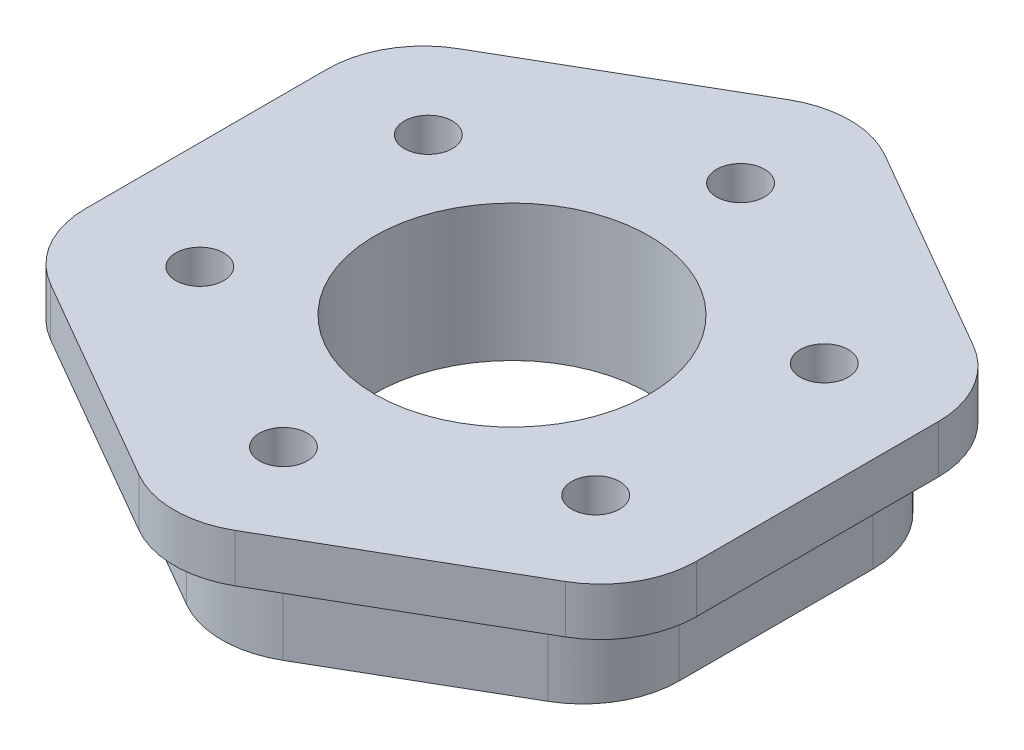
SolidWorks part; units mm, degrees
ref_plane "Front" through (0, 0, 0) normal (0, 0, 1) x (1, 0, 0)
ref_plane "Top" through (0, 0, 0) normal (0, 1, 0) x (1, 0, 0)
ref_plane "Right" through (0, 0, 0) normal (1, 0, 0) x (0, 0, -1)
sketch "Sketch1" plane through (0, 0, 0) normal (0, 1, 0) x (1, 0, 0)
  line L0 (0, 0) -> (0, -36.7195) construction
  line L1 (31.8, 18.3597) -> (0, 36.7195)
  line L2 (0, 36.7195) -> (-31.8, 18.3597)
  line L3 (-31.8, 18.3597) -> (-31.8, -18.3597)
  line L4 (-31.8, -18.3597) -> (0, -36.7195)
  line L5 (0, -36.7195) -> (31.8, -18.3597)
  line L6 (31.8, -18.3597) -> (31.8, 18.3597)
  circle A0 centre (0, 0) radius 31.8 construction
  dimension "D1" = 63.6
extrude "Boss-Extrude1" add sketch "Sketch1" along normal blind 5
fillet "Fillet1" radius 10 6 edges at (31.8, 2.5, -18.3597) (0, 2.5, -36.7195) (-31.8, 2.5, -18.3597) (-31.8, 2.5, 18.3597) (0, 2.5, 36.7195) (31.8, 2.5, 18.3597)
sketch "Sketch2" plane through (0, 5, 0) normal (0, 1, 0) x (1, 0, 0)
  line L0 (0, 23.8) -> (0, -23.8) construction
  line L1 (-20.6114, 11.9) -> (-20.6114, -11.9) construction
  line L2 (20.6114, 11.9) -> (20.6114, -11.9) construction
  line L3 (-20.6114, -11.9) -> (20.6114, -11.9) construction
  line L4 (-20.6114, -11.9) -> (20.6114, 11.9) construction
  line L5 (-20.6114, 11.9) -> (20.6114, 11.9) construction
  line L7 (20.6114, -11.9) -> (-20.6114, 11.9) construction
  circle A0 centre (0, 23.8) radius 2.5
  circle A2 centre (20.6114, 11.9) radius 2.5
  circle A3 centre (20.6114, -11.9) radius 2.5
  circle A4 centre (0, -23.8) radius 2.5
  circle A5 centre (-20.6114, -11.9) radius 2.5
  circle A6 centre (-20.6114, 11.9) radius 2.5
  circle A7 centre (0, 0) radius 14.2875
  point P21 (0, 0)
  dimension "D2" = 5
  dimension "D4" = 28.575
  dimension "D1" = 23.8
  dimension "D3" = 6
sketch "Sketch3" plane through (0, 0, 0) normal (0, -1, 0) x (1, 0, 0)
  line L0 (-20.6114, 11.9) -> (20.6114, -11.9) construction
  line L1 (27.5, 15.8771) -> (0, 31.7543)
  line L2 (0, 31.7543) -> (-27.5, 15.8771)
  line L3 (-27.5, 15.8771) -> (-27.5, -15.8771)
  line L4 (-27.5, -15.8771) -> (0, -31.7543)
  line L5 (0, -31.7543) -> (27.5, -15.8771)
  line L6 (27.5, -15.8771) -> (27.5, 15.8771)
  line L7 (0, 0) -> (0, 31.7543) construction
  line L8 (0, 31.7543) -> (0, 24.3702) construction
  circle A0 centre (0, 0) radius 27.5 construction
  dimension "D1" = 55
extrude "Boss-Extrude2" add sketch "Sketch3" along normal blind 9.2
sketch "Sketch4" plane through (0, 0, 0) normal (0, -1, 0) x (1, 0, 0)
  line L6 (27.5, 15.8771) -> (0, 31.7543) construction
  line L7 (-27.5, 15.8771) -> (-27.5, -15.8771) construction
  line L8 (0, 31.7543) -> (-27.5, 15.8771) construction
  line L9 (-27.5, -15.8771) -> (0, -31.7543) construction
  line L10 (27.5, -15.8771) -> (27.5, 15.8771) construction
  line L11 (0, -31.7543) -> (27.5, -15.8771) construction
  line L12 (4.2, -32.4471) -> (26, -19.8608)
  line L13 (30.2, -12.5862) -> (30.2, 12.5862)
  line L14 (26, 19.8608) -> (4.2, 32.4471)
  line L15 (-4.2, 32.4471) -> (-26, 19.8608)
  line L16 (-30.2, 12.5862) -> (-30.2, -12.5862)
  line L17 (-26, -19.8608) -> (-4.2, -32.4471)
  line L18 (4.2, -32.4471) -> (26, -19.8608)
  line L19 (30.2, -12.5862) -> (30.2, 12.5862)
  line L20 (26, 19.8608) -> (4.2, 32.4471)
  line L21 (-4.2, 32.4471) -> (-26, 19.8608)
  line L22 (-30.2, 12.5862) -> (-30.2, -12.5862)
  line L23 (-26, -19.8608) -> (-4.2, -32.4471)
  line L24 (27.5, 15.8771) -> (0, 31.7543)
  line L25 (-27.5, 15.8771) -> (-27.5, -15.8771)
  line L26 (0, 31.7543) -> (-27.5, 15.8771)
  line L27 (-27.5, -15.8771) -> (0, -31.7543)
  line L28 (27.5, -15.8771) -> (27.5, 15.8771)
  line L29 (0, -31.7543) -> (27.5, -15.8771)
  line L30 (4.2, -32.4471) -> (2.85, -30.1088)
  line L31 (-4.2, -32.4471) -> (-2.85, -30.1088)
  line L32 (26, -19.8608) -> (24.65, -17.5226)
  line L33 (30.2, -12.5862) -> (27.5, -12.5862)
  line L34 (30.2, 12.5862) -> (27.5, 12.5862)
  line L35 (26, 19.8608) -> (24.65, 17.5226)
  line L36 (4.2, 32.4471) -> (2.85, 30.1088)
  line L37 (-4.2, 32.4471) -> (-2.85, 30.1088)
  line L38 (-26, 19.8608) -> (-24.65, 17.5226)
  line L39 (-30.2, 12.5862) -> (-27.5, 12.5862)
  line L40 (-30.2, -12.5862) -> (-27.5, -12.5862)
  line L41 (-26, -19.8608) -> (-24.65, -17.5226)
  arc A12 (26, -19.8608) -> (30.2, -12.5862) centre (21.8, -12.5862) ccw
  arc A13 (26, -19.8608) -> (30.2, -12.5862) centre (21.8, -12.5862) ccw
  arc A14 (30.2, 12.5862) -> (26, 19.8608) centre (21.8, 12.5862) ccw
  arc A15 (30.2, 12.5862) -> (26, 19.8608) centre (21.8, 12.5862) ccw
  arc A16 (4.2, 32.4471) -> (-4.2, 32.4471) centre (0, 25.1725) ccw
  arc A17 (4.2, 32.4471) -> (-4.2, 32.4471) centre (0, 25.1725) ccw
  arc A24 (-26, 19.8608) -> (-30.2, 12.5862) centre (-21.8, 12.5862) ccw
  arc A25 (-26, 19.8608) -> (-30.2, 12.5862) centre (-21.8, 12.5862) ccw
  arc A26 (-30.2, -12.5862) -> (-26, -19.8608) centre (-21.8, -12.5862) ccw
  arc A27 (-30.2, -12.5862) -> (-26, -19.8608) centre (-21.8, -12.5862) ccw
  arc A28 (-4.2, -32.4471) -> (4.2, -32.4471) centre (0, -25.1725) ccw
  arc A29 (-4.2, -32.4471) -> (4.2, -32.4471) centre (0, -25.1725) ccw
  dimension "D1" = 1.6
extrude "Cut-Extrude1" cut sketch "Sketch4" against normal blind 3.2 contours L18 L32 L29 L30 | L41 L23 L31 L27 | L19 L34 L28 L33 | L20 L36 L24 L35 | L22 L40 L25 L39 | L21 L38 L26 L37
extrude "Cut-Extrude2" cut sketch "Sketch2" against normal through all
fillet "Fillet2" radius 10 6 edges at (27.5, -4.6, 15.8771) (0, -4.6, 31.7543) (-27.5, -4.6, 15.8771) (-27.5, -4.6, -15.8771) (27.5, -4.6, -15.8771) (0, -4.6, -31.7543)
